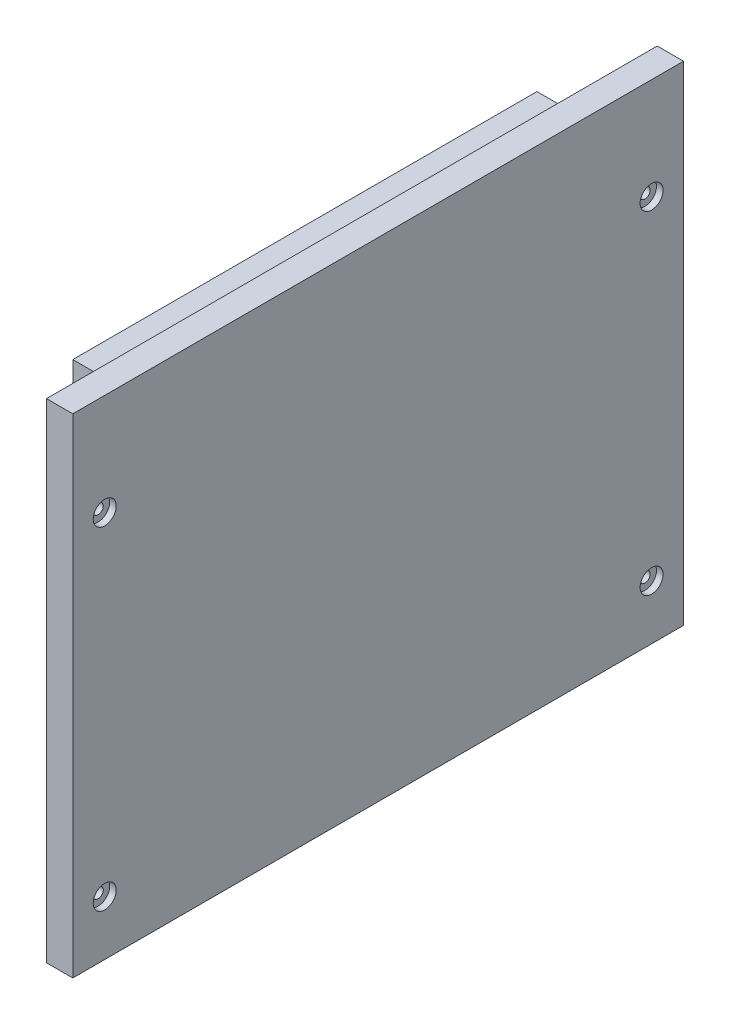
SolidWorks part; units mm, degrees
ref_plane "Front Plane" through (0, 0, 0) normal (0, 0, 1) x (1, 0, 0)
ref_plane "Top Plane" through (0, 0, 0) normal (0, 1, 0) x (1, 0, 0)
ref_plane "Right Plane" through (0, 0, 0) normal (1, 0, 0) x (0, 0, -1)
sketch "Sketch1" plane through (0, 0, 0) normal (1, 0, 0) x (0, 0, -1)
  line L1 (-175, 130) -> (150, 130)
  line L2 (-175, 130) -> (-175, -130)
  line L3 (-175, -130) -> (150, -130)
  line L4 (150, 130) -> (150, -130)
  point P4 (-175, 0)
  dimension "D1" = 150
  dimension "D2" = 175
  dimension "D3" = 260
extrude "Boss-Extrude1" add sketch "Sketch1" along normal blind 39
sketch "Sketch7" plane through (39, 0, 0) normal (1, 0, 0) x (0, 0, -1)
  circle A4 centre (133, 76) radius 6
  circle A5 centre (133, -101) radius 6
  circle A6 centre (-158, -101) radius 6
  circle A7 centre (-158, 76) radius 6
  dimension "D1" = 12
  dimension "D2" = 12
  dimension "D3" = 12
  dimension "D4" = 12
  dimension "D5" = 158
  dimension "D6" = 76
  dimension "D7" = 101
  dimension "D8" = 133
hole_wizard "CBORE for M5 Hex Head Bolt1" positions "Sketch8" profile "Sketch9" counterbore size "M5" standard "DIN"
sketch "Sketch8" plane through (39, 0, 0) normal (1, 0, 0) x (0, 0, -1)
  point P13 (133, -101)
  point P16 (133, 76)
  point P19 (-158, 76)
  point P22 (-158, -101)
sketch "Sketch9" plane through (39, -101, -133) normal (0, 1, 0) x (0, 0, -1)
  line L0 (0, 0) -> (0, 31.6524)
  line L1 (0, 31.6524) -> (2.75, 30)
  line L2 (2.75, 30) -> (2.75, 3.5)
  line L3 (2.75, 3.5) -> (6.119, 3.5)
  line L4 (6.119, 3.5) -> (6.119, 0)
  line L5 (6.119, 0) -> (0, 0)
  line L10 (0, 31.6524) -> (-2.75, 30) construction
  line L11 (0, -6.35) -> (0, 107.95) construction
  dimension "Hole Dia." = 5.5
  dimension "Hole Depth" = 30
  dimension "C'Bore Dia." = 12.238
  dimension "C'Bore Depth" = 3.5
  dimension "Drill Angle" = 118
ref_plane "Plane1" through (0, 0, -150) normal (0, 0, -1) x (-1, 0, 0)
sketch "Sketch10" plane through (0, 0, 0) normal (1, 0, 0) x (0, 0, -1)
  line L12 (150, 130) -> (111, 130)
  line L13 (150, 130) -> (150, -130)
  line L14 (150, -130) -> (111, -130)
  line L15 (111, 130) -> (111, -130)
  line L16 (150, 130) -> (-175, 130) construction
  line L17 (-136, 130) -> (-175, 130)
  line L18 (-136, 130) -> (-136, -130)
  line L19 (-136, -130) -> (-175, -130)
  line L20 (-175, 130) -> (-175, -130)
  line L21 (-175, -130) -> (150, -130) construction
  line L22 (-175, 130) -> (-175, -130) construction
  point P5 (130.5, -130)
  dimension "D1" = 39
  dimension "D2" = 39
extrude "Cut-Extrude2" cut sketch "Sketch10" along normal blind 25
ref_plane "Plane2" through (0, 130, 0) normal (0, 1, 0) x (1, 0, 0)
sketch "Sketch11" plane through (0, 130, 0) normal (0, 1, 0) x (1, 0, 0)
  line L1 (25, 111) -> (0, 111)
  line L2 (25, 111) -> (25, -136)
  line L3 (25, -136) -> (0, -136)
  line L4 (0, 111) -> (0, -136)
extrude "Cut-Extrude3" cut sketch "Sketch11" against normal blind 14
sketch "Sketch12" plane through (0, 130, 0) normal (0, 1, 0) x (1, 0, 0)
  line L0 (0, 111) -> (0, -136) construction
  line L1 (0, -136) -> (25, -136) construction
  line L2 (25, 111) -> (0, 111) construction
  circle A0 centre (14, 71.5) radius 3
  circle A1 centre (14, -96.5) radius 3
  dimension "D1" = 6
  dimension "D2" = 6
  dimension "D3" = 14
  dimension "D4" = 39.5
  dimension "D5" = 39.5
hole_wizard "Ø6.0mm Dowel Hole1" positions "Sketch13" profile "Sketch14" hole size "Ø6.0" standard "ISO"
sketch "Sketch13" plane through (0, 116, 0) normal (0, 1, 0) x (1, 0, 0)
  point P0 (14, 71.5)
  point P3 (14, -96.5)
sketch "Sketch14" plane through (14, 116, -71.5) normal (1, 0, 0) x (0, 0, 1)
  line L0 (0, 0) -> (0, 16.8026)
  line L1 (0, 16.8026) -> (3, 15)
  line L2 (3, 15) -> (3, 0)
  line L5 (3, 0) -> (0, 0)
  line L10 (0, 16.8026) -> (-3, 15) construction
  line L11 (0, -6.35) -> (0, 107.95) construction
  dimension "Hole Dia." = 6
  dimension "Hole Depth" = 15
  dimension "Drill Angle" = 118
sketch "Sketch15" plane through (0, 0, 0) normal (0, 0, 1) x (1, 0, 0)
  line L0 (25, -130) -> (25, 116) construction
  line L1 (0, -130) -> (25, -130)
  line L2 (0, -130) -> (0, -116)
  line L3 (0, -116) -> (25, -116)
  line L4 (25, -130) -> (25, -116)
  dimension "D1" = 14
extrude "Cut-Extrude4" cut sketch "Sketch15" against normal through all both and the other way through all
